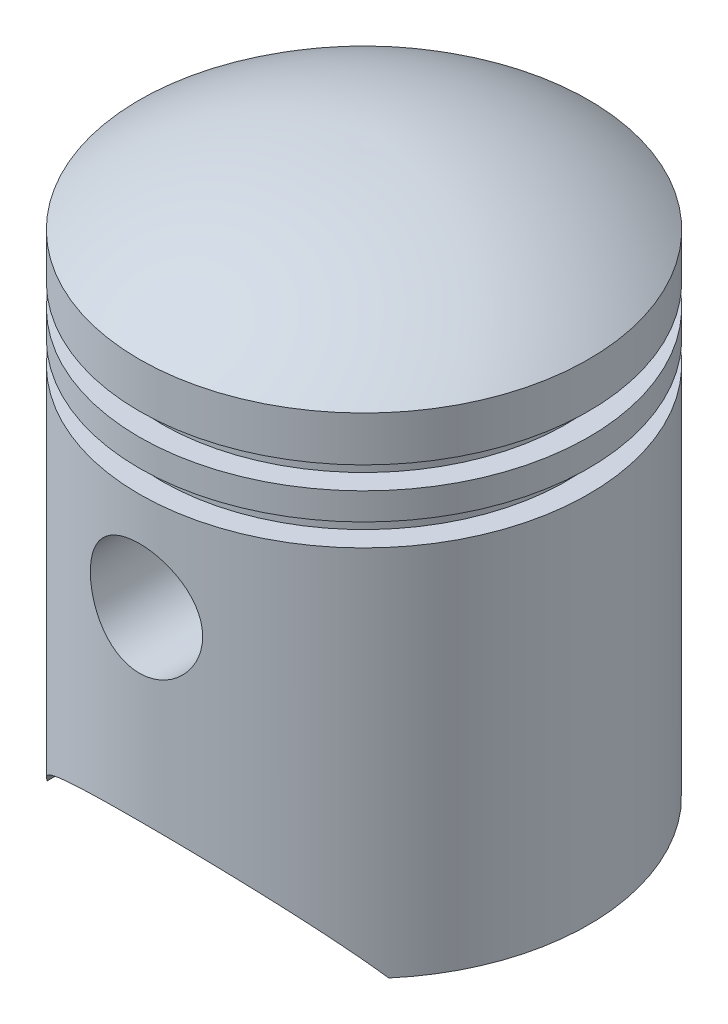
SolidWorks part; units mm, degrees
ref_plane "Front Plane" through (0, 0, 0) normal (0, 0, 1) x (1, 0, 0)
ref_plane "Top Plane" through (0, 0, 0) normal (0, 1, 0) x (1, 0, 0)
ref_plane "Right Plane" through (0, 0, 0) normal (1, 0, 0) x (0, 0, -1)
sketch "Sketch1" plane through (0, 0, 0) normal (0, 0, 1) x (1, 0, 0)
  line L0 (25, 42.9435) -> (25, 37.9435)
  line L1 (25, 37.9435) -> (22.5, 37.9435)
  line L2 (22.5, 37.9435) -> (22.5, 35.4435)
  line L3 (22.5, 35.4435) -> (25, 35.4435)
  line L4 (25, 32.4435) -> (22.5, 32.4435)
  line L5 (22.5, 32.4435) -> (22.5, 29.9435)
  line L6 (22.5, 29.9435) -> (25, 29.9435)
  line L7 (25, 35.4435) -> (25, 32.4435)
  line L8 (25, 29.9435) -> (25, -11.5565)
  line L9 (23, 27.9435) -> (23, -11.5565)
  line L10 (20.5, 27.9435) -> (23, 27.9435)
  line L11 (20.5, 33.9435) -> (20.5, 27.9435)
  line L12 (20.5, 33.9435) -> (20.5, 33.9435)
  line L13 (20.5, 33.9435) -> (20.5, 33.9435)
  line L14 (20.5, 33.9435) -> (20.5, 33.9435)
  line L15 (20.5, 39.9435) -> (20.5, 33.9435)
  line L16 (23, 39.9435) -> (20.5, 39.9435)
  line L17 (23, 41.928) -> (23, 39.9435)
  line L18 (23, -11.5565) -> (25, -11.5565)
  line L19 (0, 50.9435) -> (0, 48.9429)
  arc A0 (25, 42.9435) -> (0, 50.9435) centre (0.9839, 10.9556) ccw
  arc A1 (23, 41.928) -> (0, 48.9429) centre (0.9839, 10.9556) ccw
  arc A2 (23, 41.928) -> (0.0492, 48.9441) centre (0.9839, 10.9556) ccw construction
  dimension "D1" = 25
  dimension "D4" = 40
  dimension "D2" = 62.5
  dimension "D3" = 54.5
  dimension "D5" = 5
  dimension "D6" = 2.5
  dimension "D7" = 3
  dimension "D8" = 2
revolve "Revolve1" add sketch "Sketch1" angle 360 about L19
sketch "Sketch2" plane through (0, 0, 0) normal (0, 0, 1) x (1, 0, 0)
  line L0 (-19, -11.5565) -> (19, -11.5565)
  line L1 (-25, -11.5565) -> (25, -11.5565) construction
  circle A0 centre (0, 18.9435) radius 6.25
  arc A1 (-19, -11.5565) -> (19, -11.5565) centre (0, -24.6065) cw
  point P9 (0, -1.5565)
  dimension "D1" = 12.5
  dimension "D2" = 32
  dimension "D3" = 38
  dimension "D4" = 10
extrude "Cut-Extrude1" cut sketch "Sketch2" against normal through all both and the other way through all
sketch "Sketch3" plane through (0, 0, 0) normal (0, 0, 1) x (1, 0, 0)
  circle A0 centre (0, 18.9435) radius 7.25
  circle A1 centre (0, 18.9435) radius 6.25
  dimension "D1" = 14.5
  dimension "D2" = 12.5
extrude "Boss-Extrude1" add sketch "Sketch3" along normal up to surface (11.9257 mm away) from offset 12
mirror "Mirror1" about plane through (0, 0, 0) normal (0, 0, 1) of "Boss-Extrude1"
